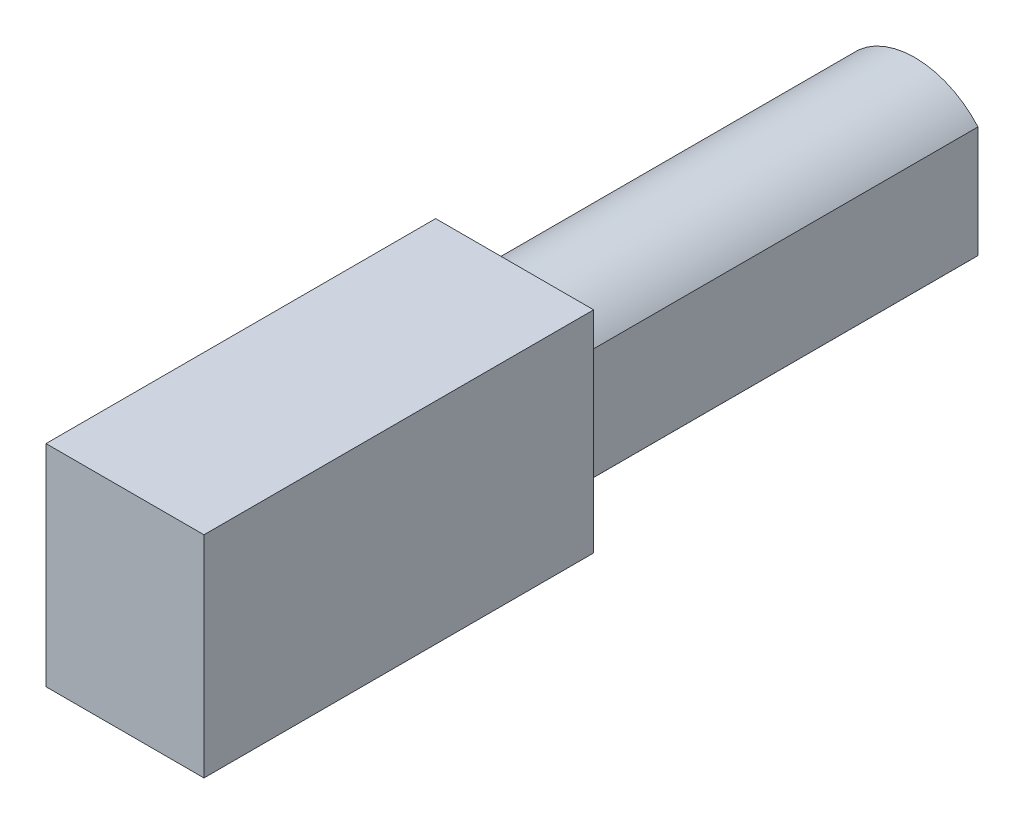
SolidWorks part; units mm, degrees
ref_plane "Front Plane" through (0, 0, 0) normal (0, 0, 1) x (1, 0, 0)
ref_plane "Top Plane" through (0, 0, 0) normal (0, 1, 0) x (1, 0, 0)
ref_plane "Right Plane" through (0, 0, 0) normal (1, 0, 0) x (0, 0, -1)
sketch "Sketch1" plane through (0, 0, 0) normal (0, 0, 1) x (1, 0, 0)
  line L1 (6, -5.2915) -> (-6, -5.2915) construction
  line L2 (6, -5.2915) -> (6, 5.2915)
  line L3 (6, 5.2915) -> (-6, 5.2915) construction
  line L4 (-6, -5.2915) -> (-6, 5.2915)
  line L5 (6, -5.2915) -> (-6, 5.2915) construction
  line L6 (6, 5.2915) -> (-6, -5.2915) construction
  arc A0 (6, 5.2915) -> (-6, 5.2915) centre (0, 0) ccw
  arc A1 (-6, -5.2915) -> (6, -5.2915) centre (0, 0) ccw
  point P7 (-5.952, 5.3454)
  dimension "D1" = 16
  dimension "D2" = 12
extrude "Boss-Extrude1" add sketch "Sketch1" along normal blind 38
sketch "Sketch2" plane through (0, 0, 38) normal (0, 0, 1) x (1, 0, 0)
  line L1 (-7.5, -10) -> (7.5, -10)
  line L2 (-7.5, -10) -> (-7.5, 10)
  line L3 (-7.5, 10) -> (7.5, 10)
  line L4 (7.5, -10) -> (7.5, 10)
  line L5 (-7.5, -10) -> (7.5, 10) construction
  line L6 (-7.5, 10) -> (7.5, -10) construction
  point P0 (0, 0)
  dimension "D1" = 15
  dimension "D2" = 20
extrude "Boss-Extrude2" add sketch "Sketch2" along normal blind 37
sketch "Sketch3" plane through (0, 0, 0) normal (0, 0, -1) x (-1, 0, 0)
  circle A0 centre (0, 0) radius 4.5
  dimension "D1" = 9
extrude "Cut-Extrude1" cut sketch "Sketch3" against normal blind 30
